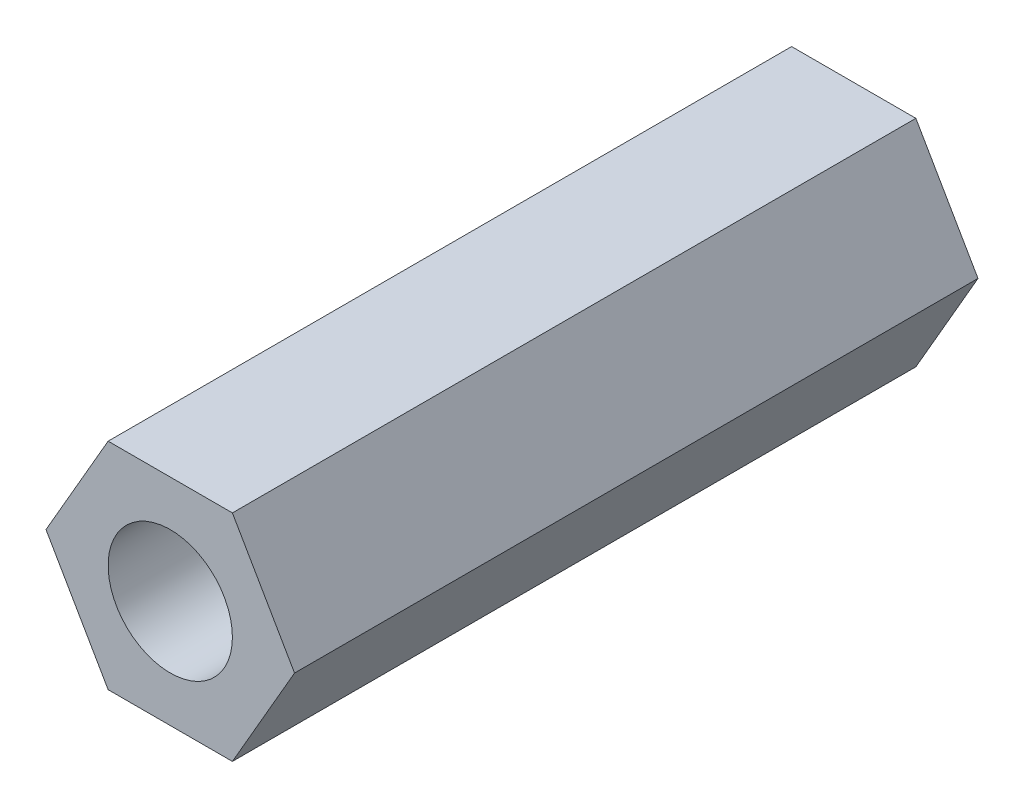
SolidWorks part; units mm, degrees
ref_plane "前视基准面" through (0, 0, 0) normal (0, 0, 1) x (1, 0, 0)
ref_plane "上视基准面" through (0, 0, 0) normal (0, 1, 0) x (1, 0, 0)
ref_plane "右视基准面" through (0, 0, 0) normal (1, 0, 0) x (0, 0, -1)
sketch "草图1" plane through (0, 0, 0) normal (0, 0, 1) x (1, 0, 0)
  line L1 (33.8, 29.8) -> (31.8, 33.2641)
  line L2 (31.8, 33.2641) -> (27.8, 33.2641)
  line L3 (27.8, 33.2641) -> (25.8, 29.8)
  line L4 (25.8, 29.8) -> (27.8, 26.3359)
  line L5 (27.8, 26.3359) -> (31.8, 26.3359)
  line L6 (31.8, 26.3359) -> (33.8, 29.8)
  circle A0 centre (29.8, 29.8) radius 3.4641 construction
  circle A1 centre (29.8, 29.8) radius 2
  dimension "D1" = 4
  dimension "D2" = 4
extrude "凸台-拉伸1" add sketch "草图1" along normal blind 22
